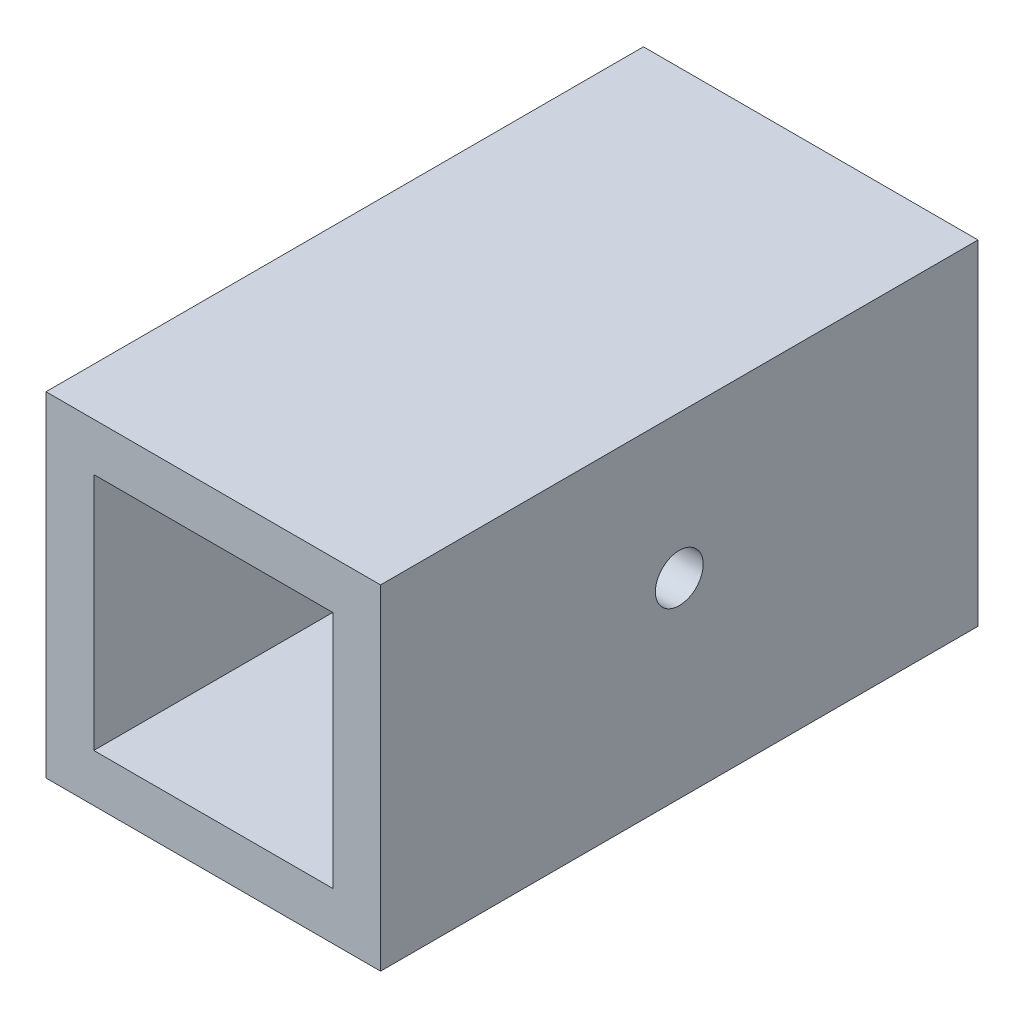
SolidWorks part; units mm, degrees
ref_plane "前视基准面" through (0, 0, 0) normal (0, 0, 1) x (1, 0, 0)
ref_plane "上视基准面" through (0, 0, 0) normal (0, 1, 0) x (1, 0, 0)
ref_plane "右视基准面" through (0, 0, 0) normal (1, 0, 0) x (0, 0, -1)
sketch "草图1" plane through (0, 0, 0) normal (0, 0, 1) x (1, 0, 0)
  line L1 (0, 0) -> (14, 0)
  line L2 (0, 0) -> (0, 14)
  line L3 (0, 14) -> (14, 14)
  line L4 (14, 0) -> (14, 14)
  line L5 (2, 2) -> (12, 2)
  line L6 (2, 2) -> (2, 12)
  line L7 (2, 12) -> (12, 12)
  line L8 (12, 2) -> (12, 12)
  point P5 (2, 2)
  point P10 (0, 0)
  point P11 (0, 0)
  point P12 (0, 0)
  point P13 (0, 0)
  point P14 (0, 0)
extrude "凸台-拉伸1" add sketch "草图1" along normal blind 10
sketch "草图2" plane through (0, 0, 10) normal (0, 0, 1) x (1, 0, 0)
  line L1 (0, 14) -> (14, 14)
  line L2 (0, 14) -> (0, 0)
  line L3 (0, 0) -> (14, 0)
  line L4 (14, 14) -> (14, 0)
  point P6 (0, 0)
extrude "凸台-拉伸2" add sketch "草图2" along normal blind 5
sketch "草图3" plane through (0, 0, 15) normal (0, 0, 1) x (1, 0, 0)
  line L1 (0, 14) -> (14, 14)
  line L2 (0, 14) -> (0, 0)
  line L3 (0, 0) -> (14, 0)
  line L4 (14, 14) -> (14, 0)
  line L5 (2, 12) -> (12, 12)
  line L6 (2, 12) -> (2, 2)
  line L7 (2, 2) -> (12, 2)
  line L8 (12, 12) -> (12, 2)
  point P6 (2, 12)
  point P11 (0, 0)
  point P12 (0, 0)
  point P13 (0, 0)
extrude "凸台-拉伸3" add sketch "草图3" along normal blind 10
sketch "草图4" plane through (14, 0, 0) normal (1, 0, 0) x (0, 0, -1)
  circle A0 centre (-11.5, 6) radius 1
  point P0 (-11.5, 6)
sketch "草图5" plane through (14, 0, 0) normal (1, 0, 0) x (0, 0, -1)
  circle A0 centre (-12.5, 6) radius 1
  point P0 (-12.5, 6)
sketch "草图6" plane through (14, 0, 0) normal (1, 0, 0) x (0, 0, -1)
  circle A0 centre (-12.5, 8) radius 1
  point P0 (-12.5, 8)
extrude "切除-拉伸1" cut sketch "草图6" against normal blind 16
